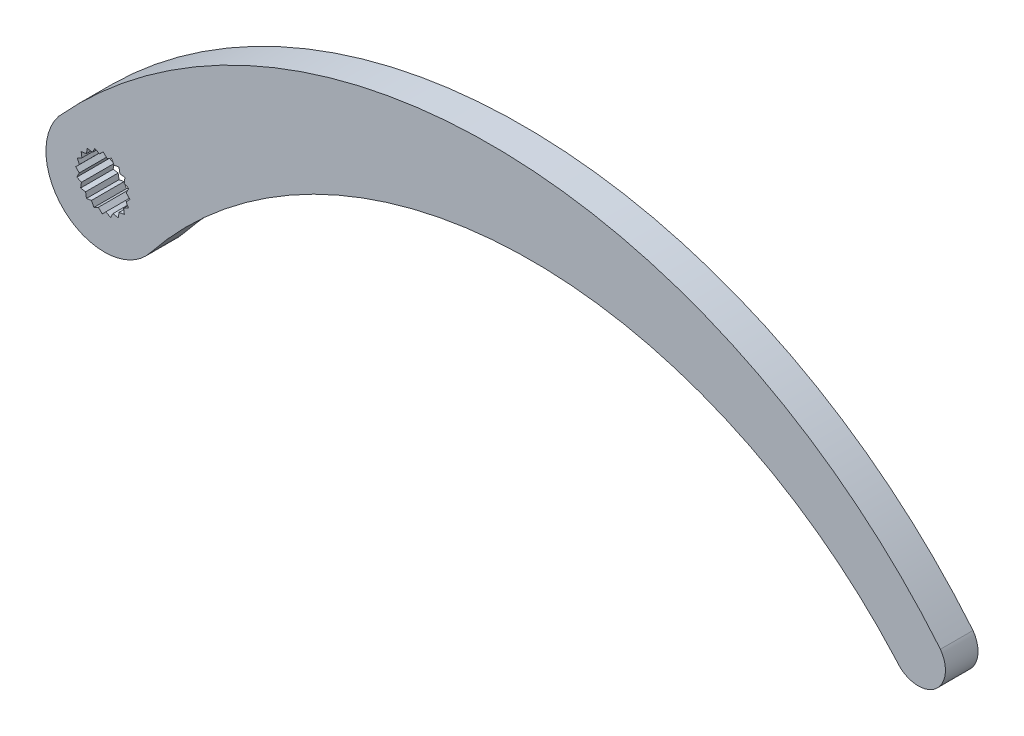
SolidWorks part; units mm, degrees
ref_plane "Front Plane" through (0, 0, 0) normal (0, 0, 1) x (1, 0, 0)
ref_plane "Top Plane" through (0, 0, 0) normal (0, 1, 0) x (1, 0, 0)
ref_plane "Right Plane" through (0, 0, 0) normal (1, 0, 0) x (0, 0, -1)
sketch "Sketch3" plane through (0, 0, 0) normal (0, 0, 1) x (1, 0, 0)
  line L0 (110.3962, 112.1736) -> (113.6462, 112.1736) construction
  line L2 (-16.8615, -7.1593) -> (-16.2359, -7.1228)
  line L3 (-1009.9587, -1.7843) -> (-11.4865, -1.7843) construction
  line L4 (-14.4953, -1.7843) -> (-14.843, -1.4366)
  line L5 (-14.4953, -1.7843) -> (-14.8488, -2.1379)
  line L6 (-14.6378, -2.5508) -> (-15.0831, -2.7783)
  line L7 (-14.6378, -2.5508) -> (-14.8488, -2.1379)
  line L8 (-15.0095, -3.2362) -> (-15.5032, -3.3155)
  line L9 (-15.0095, -3.2362) -> (-15.0831, -2.7783)
  line L10 (-15.5742, -3.7737) -> (-16.0683, -3.6971)
  line L11 (-15.5742, -3.7737) -> (-15.5032, -3.3155)
  line L12 (-16.277, -4.1112) -> (-16.7235, -3.8862)
  line L13 (-16.277, -4.1112) -> (-16.0683, -3.6971)
  line L14 (-17.0496, -4.2159) -> (-17.4051, -3.8643)
  line L15 (-17.0496, -4.2159) -> (-16.7235, -3.8862)
  line L16 (-17.8169, -4.0776) -> (-18.0468, -3.6336)
  line L17 (-17.8169, -4.0776) -> (-17.4051, -3.8643)
  line L18 (-18.5043, -3.7097) -> (-18.5863, -3.2164)
  line L19 (-18.5043, -3.7097) -> (-18.0468, -3.6336)
  line L20 (-19.0449, -3.1479) -> (-18.9711, -2.6534)
  line L21 (-19.0449, -3.1479) -> (-18.5863, -3.2164)
  line L22 (-19.3863, -2.447) -> (-19.1638, -1.9993)
  line L23 (-19.3863, -2.447) -> (-18.9711, -2.6534)
  line L24 (-19.4953, -1.675) -> (-19.1456, -1.3176)
  line L25 (-19.4953, -1.675) -> (-19.1638, -1.9993)
  line L26 (-19.3612, -0.907) -> (-18.9184, -0.6746)
  line L27 (-19.3612, -0.907) -> (-19.1456, -1.3176)
  line L28 (-18.997, -0.2176) -> (-18.5043, -0.1328)
  line L29 (-18.997, -0.2176) -> (-18.9184, -0.6746)
  line L30 (-18.4383, 0.3262) -> (-17.9434, 0.255)
  line L31 (-18.4383, 0.3262) -> (-18.5043, -0.1328)
  line L32 (-17.7393, 0.6714) -> (-17.2903, 0.4513)
  line L33 (-17.7393, 0.6714) -> (-17.9434, 0.255)
  line L34 (-16.9679, 0.7846) -> (-16.6085, 0.4369)
  line L35 (-16.9679, 0.7846) -> (-17.2903, 0.4513)
  line L36 (-16.1991, 0.6547) -> (-15.9643, 0.2133)
  line L37 (-16.1991, 0.6547) -> (-16.6085, 0.4369)
  line L38 (-15.5077, 0.2944) -> (-15.4203, -0.1979)
  line L39 (-15.5077, 0.2944) -> (-15.9643, 0.2133)
  line L40 (-14.9609, -0.2613) -> (-15.0293, -0.7566)
  line L41 (-14.9609, -0.2613) -> (-15.4203, -0.1979)
  line L42 (-14.6118, -0.9584) -> (-14.843, -1.4366)
  line L43 (-14.6118, -0.9584) -> (-15.0293, -0.7566)
  line L44 (-16.8615, -1.7843) -> (-3.6865, -1.7843) construction
  line L45 (236.3236, -203.0298) -> (-21.0693, 1.5602) construction
  line L46 (-710.5696, -634.748) -> (23.3719, -33.764) construction
  line L47 (58.1017, -1.7843) -> (56.0627, -3.2309) construction
  line L51 (58.1292, -5.3032) -> (58.1073, -5.3212) construction
  line L55 (714.1786, -788.2626) -> (236.3236, -203.0298) construction
  line L85 (58.1073, -5.3212) -> (58.1292, -5.3032) construction
  line L86 (30.2848, -39.2588) -> (-769.5461, -692.3378) construction
  arc A0 (-21.0693, 1.5602) -> (-16.8615, -7.1593) centre (-16.8615, -1.7843) ccw
  arc A12 (-21.0693, 1.5602) -> (-12.6538, -5.1289) centre (-16.8615, -1.7843) ccw
  arc A16 (54.2707, -0.9236) -> (54.2709, -0.9238) centre (23.1385, -41.4569) cw
  arc A17 (56.0627, -3.2309) -> (60.1407, -0.3378) centre (58.1017, -1.7843) ccw
  arc A18 (-12.6538, -5.1289) -> (56.0627, -3.2309) centre (22.5025, -33.073) cw
  arc A19 (-21.0693, 1.5602) -> (60.1407, -0.3378) centre (18.716, -34.4641) cw
  point P10 (20.7635, -1.7843)
  point P22 (17.4635, -1.7843)
  point P25 (-9.8314, -1.6219)
  point P27 (-22.2365, -1.7843)
  point P60 (-12.6538, -5.1289)
  dimension "D2" = 10.75
  dimension "D3" = 5
  dimension "D4" = 0.5
  dimension "D5" = 0.4917
  dimension "D1" = 3.25
  dimension "D13" = 43
  dimension "D14" = 3.3
  dimension "D15" = 5
  dimension "D17" = 45
  dimension "D18" = 45
  dimension "D19" = 20
extrude "Boss-Extrude1" add sketch "Sketch3" along normal blind 3
